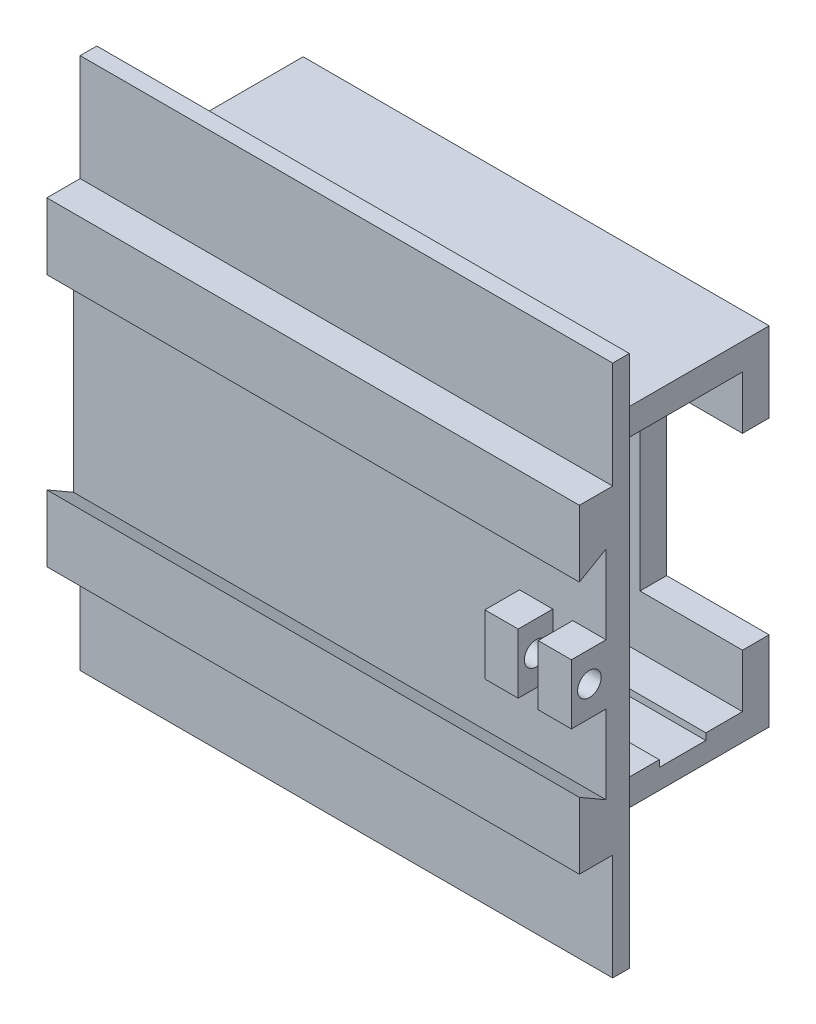
SolidWorks part; units mm, degrees
material "ABS"
ref_plane "Front Plane" through (0, 0, 0) normal (0, 0, 1) x (1, 0, 0)
ref_plane "Top Plane" through (0, 0, 0) normal (0, 1, 0) x (1, 0, 0)
ref_plane "Right Plane" through (0, 0, 0) normal (1, 0, 0) x (0, 0, -1)
sketch "Sketch1" plane through (0, 0, 0) normal (0, 0, 1) x (1, 0, 0)
  line L1 (-50.8, -50.8) -> (50.8, -50.8)
  line L2 (-50.8, -50.8) -> (-50.8, 50.8)
  line L3 (-50.8, 50.8) -> (50.8, 50.8)
  line L4 (50.8, -50.8) -> (50.8, 50.8)
  line L5 (-50.8, -50.8) -> (50.8, 50.8) construction
  line L6 (-50.8, 50.8) -> (50.8, -50.8) construction
  point P0 (0, 0)
  dimension "D1" = 101.6
  dimension "D2" = 101.6
extrude "Extrude1" add sketch "Sketch1" along normal blind 3.175
sketch "Sketch2" plane through (0, 0, 3.175) normal (0, 0, 1) x (1, 0, 0)
  line L0 (50.8, -50.8) -> (50.8, 50.8) construction
  line L1 (-50.8, -30.48) -> (50.8, -30.48)
  line L2 (-50.8, -30.48) -> (-50.8, 30.48)
  line L3 (-50.8, 30.48) -> (50.8, 30.48)
  line L4 (50.8, -30.48) -> (50.8, 30.48)
  line L5 (-50.8, -30.48) -> (50.8, 30.48) construction
  line L6 (-50.8, 30.48) -> (50.8, -30.48) construction
  point P0 (0, 0)
  dimension "D1" = 60.96
extrude "Extrude2" add sketch "Sketch2" along normal blind 6.35
sketch "Sketch3" plane through (50.8, 0, 0) normal (1, 0, 0) x (0, 0, -1)
  line L0 (-9.525, -17.78) -> (-4.445, -20.7129)
  line L1 (-9.525, -30.48) -> (-9.525, 30.48) construction
  line L2 (-4.445, -20.7129) -> (-4.445, 20.7129)
  line L3 (-4.445, 20.7129) -> (-9.525, 17.78)
  line L4 (-9.525, 17.78) -> (-9.525, -17.78)
  line L6 (-9.525, -17.78) -> (-9.525, -30.48) construction
  line L7 (-9.525, 30.48) -> (-9.525, 17.78) construction
  dimension "D1" = 60
  dimension "D2" = 5.08
  dimension "D3" = 12.7
  dimension "D4" = 12.7
extrude "Extrude3" cut sketch "Sketch3" against normal through all
sketch "Sketch4" plane through (0, 0, 0) normal (0, 0, -1) x (-1, 0, 0)
  line L1 (46.99, -33.147) -> (-41.91, -33.147)
  line L2 (46.99, -33.147) -> (46.99, 33.147)
  line L3 (46.99, 33.147) -> (-41.91, 33.147)
  line L4 (-41.91, -33.147) -> (-41.91, 33.147)
  line L5 (46.99, -33.147) -> (-41.91, 33.147) construction
  line L6 (46.99, 33.147) -> (-41.91, -33.147) construction
  line L7 (50.8, 50.8) -> (50.8, -50.8) construction
  point P0 (2.54, 0)
  dimension "D1" = 66.294
  dimension "D2" = 88.9
  dimension "D3" = 3.81
extrude "Extrude4" add sketch "Sketch4" along normal blind 35.56
sketch "Sketch5" plane through (41.91, 0, 0) normal (1, 0, 0) x (0, 0, -1)
  line L0 (35.56, 33.147) -> (35.56, -33.147) construction
  line L2 (3.175, -28.067) -> (3.175, 28.067)
  line L3 (3.175, 28.067) -> (30.48, 28.067)
  line L4 (30.48, -28.067) -> (30.48, 28.067)
  line L5 (30.48, 28.067) -> (30.48, 33.147) construction
  line L6 (35.56, 33.147) -> (0, 33.147) construction
  line L7 (30.48, -28.067) -> (30.48, -33.147) construction
  line L8 (35.56, -33.147) -> (0, -33.147) construction
  line L9 (0, 33.147) -> (0, -33.147) construction
  line L10 (3.175, -28.067) -> (30.48, -28.067)
  dimension "D1" = 5.08
  dimension "D2" = 27.305
  dimension "D3" = 3.175
  dimension "D4" = 56.134
extrude "Extrude5" cut sketch "Sketch5" against normal through all
sketch "Sketch6" plane through (0, 0, -3.175) normal (0, 0, -1) x (-1, 0, 0)
  line L0 (46.99, 28.067) -> (-41.91, 28.067) construction
  line L1 (46.99, -28.067) -> (43.815, -28.067)
  line L2 (46.99, -28.067) -> (46.99, 28.067)
  line L3 (46.99, 28.067) -> (43.815, 28.067)
  line L4 (43.815, -28.067) -> (43.815, 28.067)
  dimension "D1" = 3.175
extrude "Extrude6" add sketch "Sketch6" along normal blind 12.7
sketch "Sketch7" plane through (41.91, 0, 0) normal (1, 0, 0) x (0, 0, -1)
  line L0 (3.175, -28.067) -> (30.48, -28.067) construction
  line L1 (14.605, -28.067) -> (23.495, -28.067)
  line L2 (14.605, -28.067) -> (14.605, -29.337)
  line L3 (14.605, -29.337) -> (23.495, -29.337)
  line L4 (23.495, -28.067) -> (23.495, -29.337)
  line L5 (3.175, 28.067) -> (3.175, -28.067) construction
  dimension "D1" = 8.89
  dimension "D2" = 11.43
  dimension "D3" = 1.27
extrude "Extrude7" cut sketch "Sketch7" against normal blind 79.375
sketch "Sketch8" plane through (41.91, 0, 0) normal (1, 0, 0) x (0, 0, -1)
  line L0 (30.48, -28.067) -> (30.48, 28.067) construction
  line L1 (30.48, 17.907) -> (35.56, 17.907)
  line L2 (30.48, 17.907) -> (30.48, -17.907)
  line L3 (30.48, -17.907) -> (35.56, -17.907)
  line L4 (35.56, 17.907) -> (35.56, -17.907)
  line L5 (35.56, 33.147) -> (35.56, -33.147) construction
  line L6 (23.495, -28.067) -> (30.48, -28.067) construction
  line L7 (30.48, 28.067) -> (3.175, 28.067) construction
  dimension "D1" = 10.16
  dimension "D2" = 10.16
extrude "Extrude8" cut sketch "Sketch8" against normal blind 19.558
sketch "Sketch9" plane through (0, -33.147, 0) normal (0, -1, 0) x (1, 0, 0)
  line L0 (41.91, -35.56) -> (-46.99, -35.56) construction
  line L1 (-46.99, -35.56) -> (-46.99, 0) construction
  point P0 (12.8016, -20.066)
  dimension "D1" = 15.494
  dimension "D2" = 59.7916
hole_wizard "5/16 Clearance Hole1" positions "3DSketch1" profile "Sketch10" hole size "5/16" standard "Ansi Inch"
sketch3d "3DSketch1"
  point P0 (12.8016, -33.147, -20.066)
sketch "Sketch10" plane through (12.8016, -33.147, -20.066) normal (1, 0, 0) x (0, 0, -1)
  line L0 (0, 0) -> (0, 15.4875)
  line L1 (0, 15.4875) -> (4.2164, 12.954)
  line L2 (4.2164, 12.954) -> (4.2164, 0)
  line L5 (4.2164, 0) -> (0, 0)
  line L10 (0, 15.4875) -> (-4.2164, 12.954) construction
  line L11 (0, -6.35) -> (0, 107.95) construction
  dimension "Hole Dia." = 8.4328
  dimension "Hole Depth" = 12.954
  dimension "Drill Angle" = 118
sketch "Sketch11" plane through (0, 0, 4.445) normal (0, 0, 1) x (1, 0, 0)
  line L0 (50.8, 0) -> (50.8, -5.715)
  line L1 (50.8, -20.7129) -> (50.8, 20.7129) construction
  line L2 (50.8, -5.715) -> (44.45, -5.715)
  line L3 (44.45, -5.715) -> (44.45, 5.715)
  line L4 (44.45, 5.715) -> (50.8, 5.715)
  line L5 (50.8, 5.715) -> (50.8, 0)
  dimension "D1" = 6.35
  dimension "D2" = 11.43
extrude "Extrude9" add sketch "Sketch11" along normal blind 6.604
sketch "Sketch13" plane through (50.8, 0, 0) normal (1, 0, 0) x (0, 0, -1)
  line L0 (-7.62, -5.715) -> (-7.62, 5.715) construction
  line L4 (-4.445, -20.7129) -> (-4.445, -5.715) construction
  point P6 (-7.62, 0)
  dimension "D1" = 3.175
hole_wizard "#8 Clearance Hole1" positions "3DSketch2" profile "Sketch15" hole size "#8" standard "Ansi Inch" end condition through all
sketch3d "3DSketch2"
  point P0 (50.8, 0, 7.62)
sketch "Sketch15" plane through (50.8, 0, 7.62) normal (0, 1, 0) x (0, 0, -1)
  line L0 (0, 0) -> (0, 91.44)
  line L1 (0, 91.44) -> (2.2479, 91.44)
  line L2 (2.2479, 91.44) -> (2.2479, 0)
  line L5 (2.2479, 0) -> (0, 0)
  line L11 (0, -6.35) -> (0, 107.95) construction
  dimension "Thru Hole Dia." = 4.4958
  dimension "Thru Hole Depth" = 91.44
pattern_linear "LPattern1" count 2 spacing 10.16 along (-1, 0, 0) of "Extrude9", "#8 Clearance Hole1"
